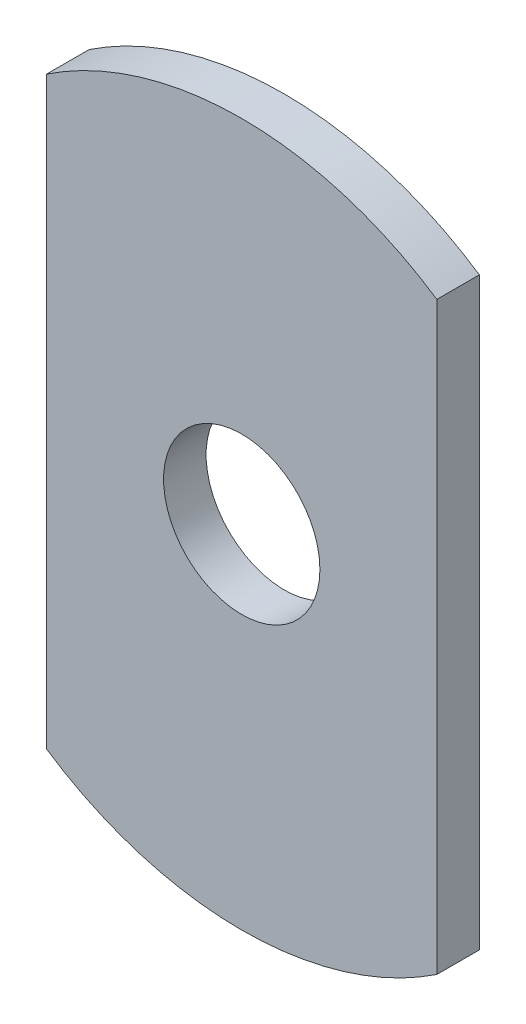
SolidWorks part; units mm, degrees
ref_plane "Front Plane" through (0, 0, 0) normal (0, 0, 1) x (1, 0, 0)
ref_plane "Top Plane" through (0, 0, 0) normal (0, 1, 0) x (1, 0, 0)
ref_plane "Right Plane" through (0, 0, 0) normal (1, 0, 0) x (0, 0, -1)
sketch "Sketch1" plane through (0, 0, 0) normal (0, 0, 1) x (1, 0, 0)
  line L0 (-3.9624, 5.9365) -> (-3.9624, -5.9365)
  line L1 (0, -7.1374) -> (0, 7.1374) construction
  line L2 (3.9624, 5.9365) -> (3.9624, -5.9365)
  circle A0 centre (0, 0) radius 1.5875
  arc A1 (-3.9624, -5.9365) -> (3.9624, -5.9365) centre (0, 0) ccw
  arc A2 (3.9624, 5.9365) -> (-3.9624, 5.9365) centre (0, 0) ccw
  dimension "ID" = 3.175
  dimension "OD" = 14.2748
  dimension "B" = 7.9248
extrude "Extrude1" add sketch "Sketch1" against normal blind 0.8636
